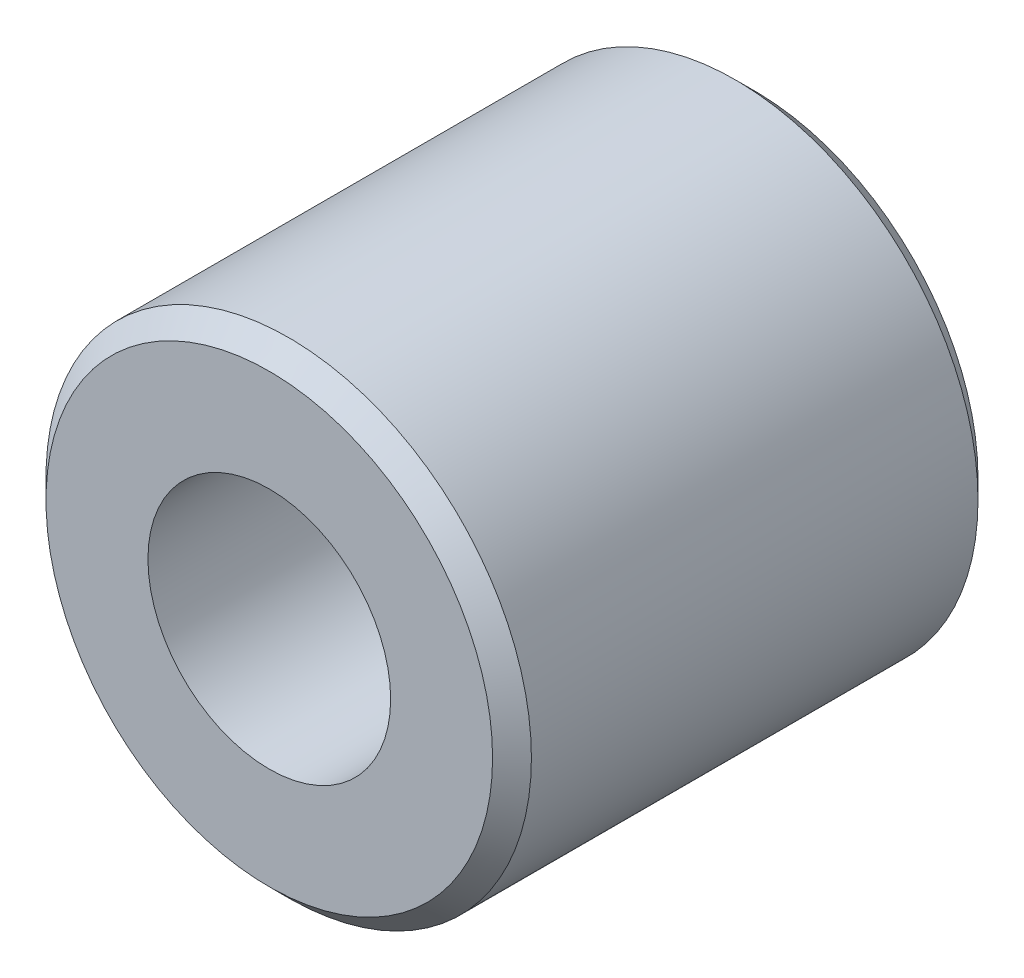
SolidWorks part; units mm, degrees
material "AISI 304"
ref_plane "前视基准面" through (0, 0, 0) normal (0, 0, 1) x (1, 0, 0)
ref_plane "上视基准面" through (0, 0, 0) normal (0, 1, 0) x (1, 0, 0)
ref_plane "右视基准面" through (0, 0, 0) normal (1, 0, 0) x (0, 0, -1)
other "Configuration Table"
sketch "草图1" plane through (0, 0, 0) normal (0, 0, 1) x (1, 0, 0)
  circle A0 centre (0, 0) radius 1.25
  circle A1 centre (0, 0) radius 2.5
  dimension "D1" = 2.5
  dimension "D2" = 5
extrude "凸台-拉伸1" add sketch "草图1" along normal blind 5
cosmetic thread "装饰螺纹线1"
cosmetic thread "装饰螺纹线2"
chamfer "倒角1" distance 0.2 angle 45 2 edges at (2.5, 0, 5) (2.5, 0, 0)
